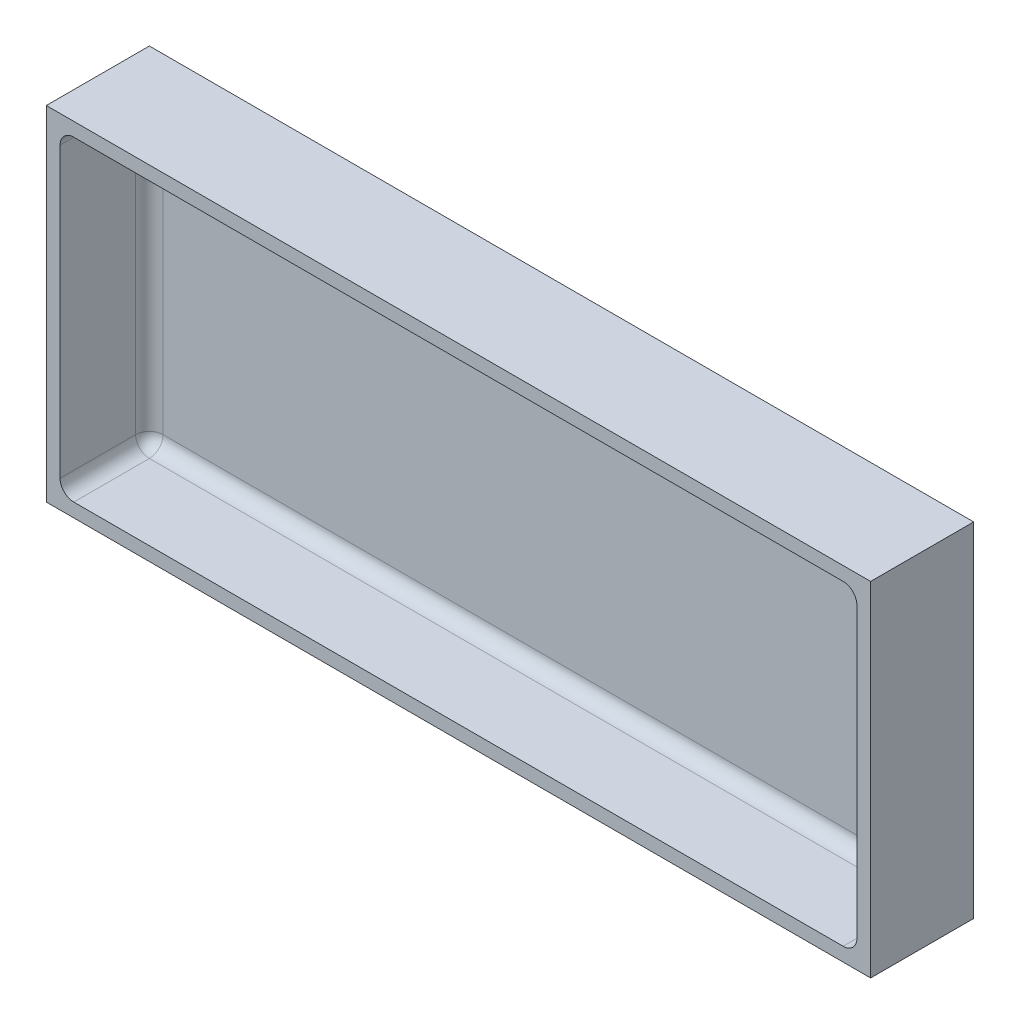
SolidWorks part; units mm, degrees
material "Alumina"
ref_plane "Front Plane" through (0, 0, 0) normal (0, 0, 1) x (1, 0, 0)
ref_plane "Top Plane" through (0, 0, 0) normal (0, 1, 0) x (1, 0, 0)
ref_plane "Right Plane" through (0, 0, 0) normal (1, 0, 0) x (0, 0, -1)
sketch "Sketch1" plane through (0, 0, 0) normal (0, 0, 1) x (1, 0, 0)
  line L1 (-60, -25) -> (60, -25)
  line L2 (-60, -25) -> (-60, 25)
  line L3 (-60, 25) -> (60, 25)
  line L4 (60, -25) -> (60, 25)
  line L5 (-60, -25) -> (60, 25) construction
  line L6 (-60, 25) -> (60, -25) construction
  point P0 (0, 0)
  dimension "D1" = 120
  dimension "D2" = 50
extrude "Boss-Extrude1" add sketch "Sketch1" against normal blind 15
shell "Shell1" thickness 2
fillet "Fillet1" radius 2 8 edges at (-58, 23, -6.5) (-58, -23, -6.5) (0, -23, -13) (-58, 0, -13) (0, 23, -13) (58, 0, -13) (58, 23, -6.5) (58, -23, -6.5)
